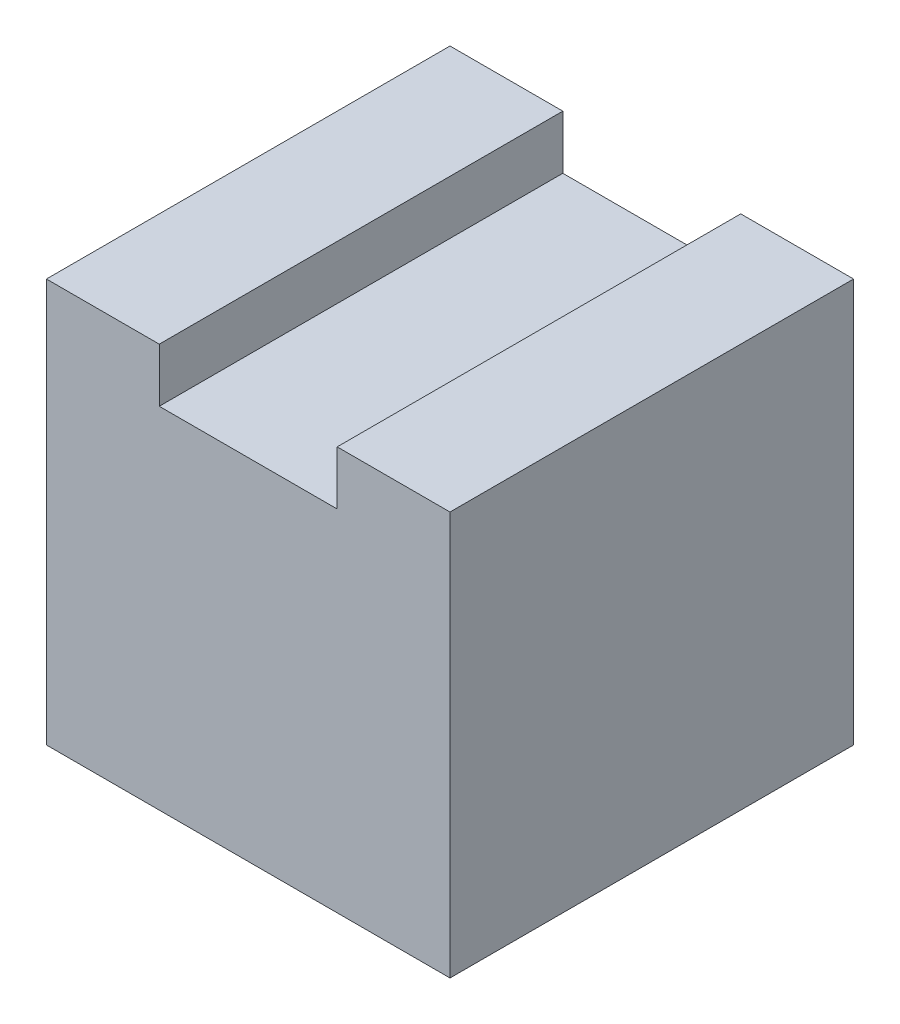
SolidWorks part; units mm, degrees
ref_plane "Front Plane" through (0, 0, 0) normal (0, 0, 1) x (1, 0, 0)
ref_plane "Top Plane" through (0, 0, 0) normal (0, 1, 0) x (1, 0, 0)
ref_plane "Right Plane" through (0, 0, 0) normal (1, 0, 0) x (0, 0, -1)
sketch "Sketch1" plane through (0, 0, 0) normal (0, 1, 0) x (1, 0, 0)
  line L1 (150, -150) -> (-150, -150)
  line L2 (150, -150) -> (150, 150)
  line L3 (150, 150) -> (-150, 150)
  line L4 (-150, -150) -> (-150, 150)
  line L5 (150, -150) -> (-150, 150) construction
  line L6 (150, 150) -> (-150, -150) construction
  point P0 (0, 0)
extrude "Boss-Extrude1" add sketch "Sketch1" along normal blind 300
sketch "Sketch3" plane through (0, 0, 0) normal (0, 1, 0) x (1, 0, 0)
  circle A0 centre (-63.2724, -59.7572) radius 79.8955
  point P2 (-63.2724, -59.7572)
extrude "Cut-Extrude1" cut sketch "Sketch3" along normal blind 100 contours A0
sketch "Sketch8" plane through (0, 0, 0) normal (0, -1, 0) x (1, 0, 0)
  circle A0 centre (-70.7162, -86.2241) radius 50
  point P2 (-60.7911, -85.397)
  point P3 (-70.7162, -86.2241)
extrude "Cut-Extrude3" cut sketch "Sketch8" against normal blind 100 contours A0
sketch "Sketch9" plane through (0, 0, 0) normal (0, -1, 0) x (1, 0, 0)
  line L1 (128.1989, -137.5037) -> (54.5879, -137.5037)
  line L2 (128.1989, -137.5037) -> (128.1989, 137.5037)
  line L3 (128.1989, 137.5037) -> (54.5879, 137.5037)
  line L4 (54.5879, -137.5037) -> (54.5879, 137.5037)
  line L5 (128.1989, -137.5037) -> (54.5879, 137.5037) construction
  line L6 (128.1989, 137.5037) -> (54.5879, -137.5037) construction
  point P0 (91.3934, 0)
extrude "Cut-Extrude4" cut sketch "Sketch9" against normal blind 80 contours L4 L3 L2 L1
sketch "Sketch11" plane through (0, 300, 0) normal (0, 1, 0) x (1, 0, 0)
  line L0 (150, 150) -> (-150, 150) construction
  line L1 (66.1284, -150) -> (-66.1284, -150)
  line L2 (66.1284, -150) -> (66.1284, 150)
  line L3 (66.1284, 150) -> (-66.1284, 150)
  line L4 (-66.1284, -150) -> (-66.1284, 150)
  line L5 (66.1284, -150) -> (-66.1284, 150) construction
  line L6 (66.1284, 150) -> (-66.1284, -150) construction
  point P0 (0, 0)
extrude "Cut-Extrude6" cut sketch "Sketch11" against normal blind 40
